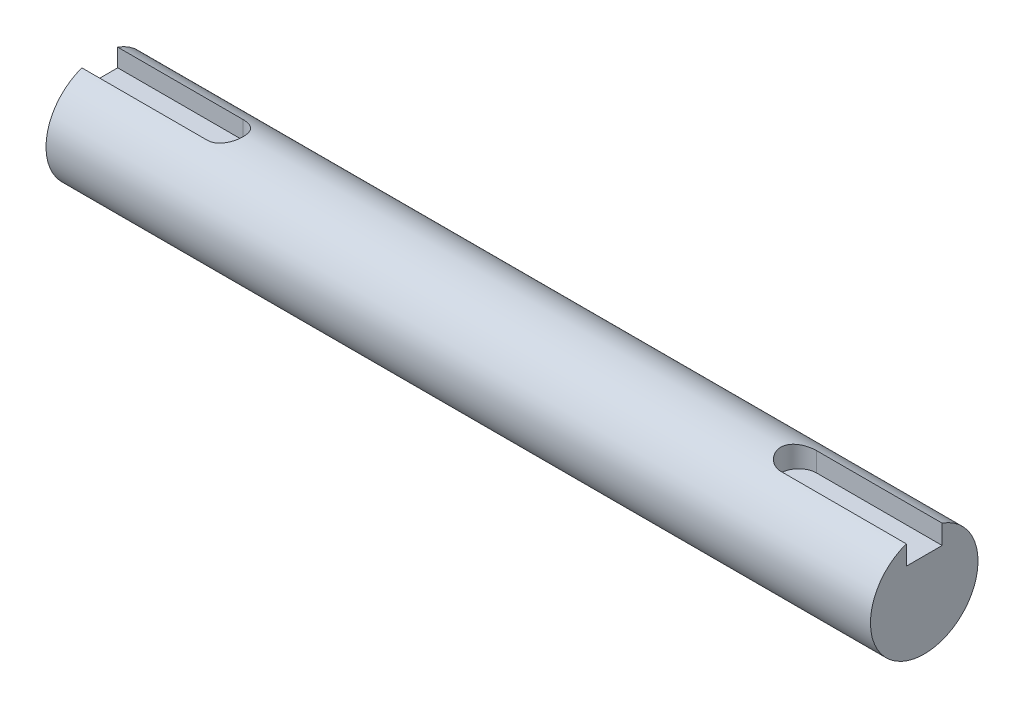
SolidWorks part; units mm, degrees
material "AISI 1045 Steel, cold drawn"
ref_plane "Frontal Plane" through (0, 0, 0) normal (0, 0, 1) x (1, 0, 0)
ref_plane "Horizontal Plane" through (0, 0, 0) normal (0, 1, 0) x (1, 0, 0)
ref_plane "Profile Plane" through (0, 0, 0) normal (1, 0, 0) x (0, 0, -1)
sketch "Sketch1" plane through (0, 0, 0) normal (1, 0, 0) x (0, 0, -1)
  circle A0 centre (0, 0) radius 7.5
  dimension "D1" = 15
extrude "Boss-Extrude1" add sketch "Sketch1" along normal blind 115
sketch "Sketch7" plane through (0, 0, 0) normal (-1, 0, 0) x (0, 0, 1)
  line L0 (-2.5, 7.0711) -> (2.5, 7.0711) construction
  line L1 (0, 7.0711) -> (0, 7.5) construction
  arc A0 (2.5, 7.0711) -> (-2.5, 7.0711) centre (0, 0) cw construction
  circle A1 centre (0, 0) radius 7.5 construction
  dimension "D1" = 5
ref_plane "Plane2" through (0, 7.0711, 0) normal (0, 1, 0) x (1, 0, 0)
sketch "Sketch8" plane through (0, 7.0711, 0) normal (0, 1, 0) x (1, 0, 0)
  line L0 (0, 0) -> (17.5, 0) construction
  line L1 (0, 2.5) -> (17.5, 2.5)
  line L2 (0, -2.5) -> (17.5, -2.5)
  arc A0 (0, 2.5) -> (0, -2.5) centre (0, 0) ccw
  arc A1 (17.5, -2.5) -> (17.5, 2.5) centre (17.5, 0) ccw
  point P3 (8.75, 0)
  dimension "D1" = 17.5
  dimension "D2" = 5
extrude "Cut-Extrude3" cut sketch "Sketch8" against normal blind 12.5 from offset 10
sketch "Sketch9" plane through (0, 7.0711, 0) normal (0, 1, 0) x (1, 0, 0)
  line L0 (115, 0) -> (97.5, 0) construction
  line L1 (115, -7.5) -> (115, 7.5) construction
  line L2 (115, -2.5) -> (97.5, -2.5)
  line L3 (115, 2.5) -> (97.5, 2.5)
  arc A0 (115, -2.5) -> (115, 2.5) centre (115, 0) ccw
  arc A1 (97.5, 2.5) -> (97.5, -2.5) centre (97.5, 0) ccw
  point P5 (106.25, 0)
  dimension "D1" = 5
  dimension "D2" = 17.5
extrude "Cut-Extrude4" cut sketch "Sketch9" against normal blind 12.7 from offset 10
